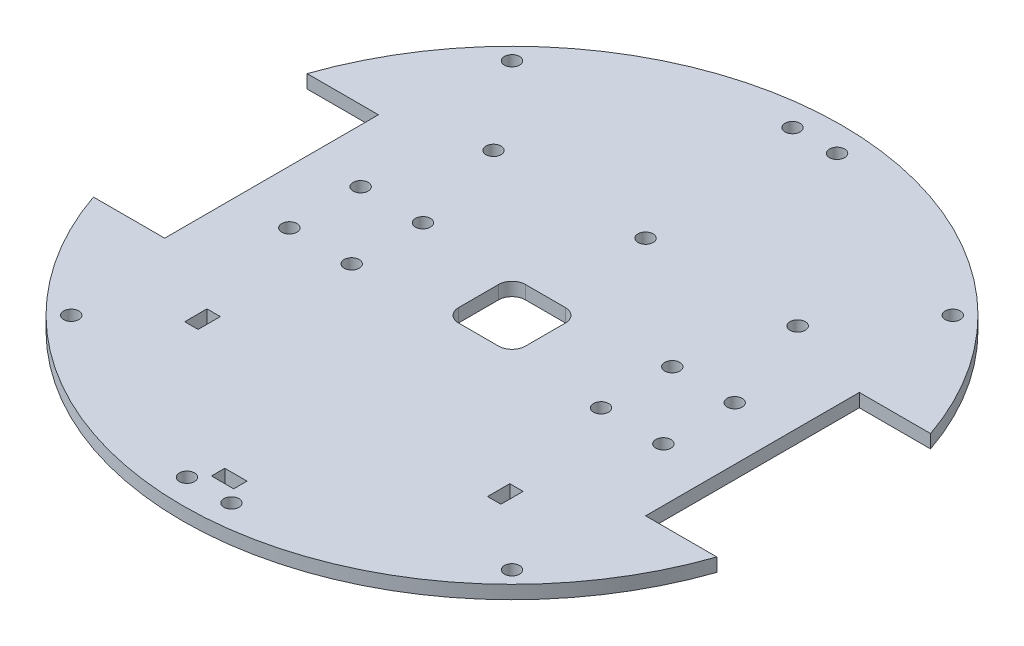
SolidWorks part; units mm, degrees
ref_plane "前视基准面" through (0, 0, 0) normal (0, 0, 1) x (1, 0, 0)
ref_plane "上视基准面" through (0, 0, 0) normal (0, 1, 0) x (1, 0, 0)
ref_plane "右视基准面" through (0, 0, 0) normal (1, 0, 0) x (0, 0, -1)
other "Configuration Table"
sketch "草图1" plane through (0, 0, 0) normal (0, 1, 0) x (1, 0, 0)
  line L0 (-74, 0) -> (74, 0) construction
  line L1 (0, 74) -> (0, -74) construction
  line L2 (35, -13) -> (35, 13) construction
  line L3 (19.5, -13) -> (50.5, -13) construction
  line L4 (19.5, -13) -> (19.5, 13) construction
  line L5 (19.5, 13) -> (50.5, 13) construction
  line L6 (50.5, -13) -> (50.5, 13) construction
  line L7 (19.5, -13) -> (50.5, 13) construction
  line L8 (19.5, 13) -> (50.5, -13) construction
  line L9 (49, 13) -> (49, -13) construction
  line L10 (70, 24) -> (54, 24)
  line L11 (54, 24) -> (54, -24)
  line L12 (54, -24) -> (70, -24)
  line L13 (-54, -24) -> (-70, -24)
  line L14 (-54, 24) -> (-54, -24)
  line L15 (-70, 24) -> (-54, 24)
  line L16 (35.5, -33) -> (32.5, -33)
  line L17 (-4.5, -7.5) -> (4.5, -7.5)
  line L18 (-7.5, -4.5) -> (-7.5, 4.5)
  line L19 (-4.5, 7.5) -> (4.5, 7.5)
  line L20 (7.5, -4.5) -> (7.5, 4.5)
  line L21 (-7.5, -7.5) -> (7.5, 7.5) construction
  line L22 (-7.5, 7.5) -> (7.5, -7.5) construction
  line L23 (-45.15, 18) -> (45.15, 18) construction
  line L24 (-45.15, 18) -> (-45.15, 55) construction
  line L25 (-45.15, 55) -> (45.15, 55) construction
  line L26 (45.15, 18) -> (45.15, 55) construction
  line L27 (-45.15, 18) -> (45.15, 55) construction
  line L28 (-45.15, 55) -> (45.15, 18) construction
  line L29 (-34, -63.5) -> (34, -63.5) construction
  line L30 (-34, -63.5) -> (-34, -7.5) construction
  line L31 (-34, -7.5) -> (34, -7.5) construction
  line L32 (34, -63.5) -> (34, -7.5) construction
  line L33 (-34, -63.5) -> (34, -7.5) construction
  line L34 (-34, -7.5) -> (34, -63.5) construction
  line L35 (-2.5, -65) -> (2.5, -65)
  line L36 (-2.5, -65) -> (-2.5, -62)
  line L37 (-2.5, -62) -> (2.5, -62)
  line L38 (2.5, -65) -> (2.5, -62)
  line L39 (-2.5, -65) -> (2.5, -62) construction
  line L40 (-2.5, -62) -> (2.5, -65) construction
  line L41 (-35.5, -38) -> (-32.5, -38)
  line L42 (-35.5, -38) -> (-35.5, -33)
  line L43 (-35.5, -33) -> (-32.5, -33)
  line L44 (-32.5, -38) -> (-32.5, -33)
  line L45 (-35.5, -38) -> (-32.5, -33) construction
  line L46 (-35.5, -33) -> (-32.5, -38) construction
  line L47 (32.5, -38) -> (32.5, -33)
  line L48 (35.5, -38) -> (32.5, -38)
  line L49 (35.5, -38) -> (35.5, -33)
  line L50 (-49.4975, -49.4975) -> (0, 0) construction
  circle A0 centre (0, 0) radius 74
  circle A1 centre (28, 8) radius 1.7
  circle A2 centre (42, 8) radius 1.7
  circle A3 centre (42, -8) radius 1.7
  circle A4 centre (28, -8) radius 1.7
  circle A5 centre (-42, -8) radius 1.7
  circle A6 centre (-28, -8) radius 1.7
  circle A7 centre (-42, 8) radius 1.7
  circle A8 centre (-28, 8) radius 1.7
  arc A9 (-4.5, 7.5) -> (-7.5, 4.5) centre (-4.5, 4.5) ccw
  arc A10 (7.5, 4.5) -> (4.5, 7.5) centre (4.5, 4.5) ccw
  arc A11 (4.5, -7.5) -> (7.5, -4.5) centre (4.5, -4.5) ccw
  arc A12 (-4.5, -7.5) -> (-7.5, -4.5) centre (-4.5, -4.5) cw
  circle A13 centre (0, 30) radius 1.7
  circle A14 centre (34.15, 30) radius 1.7
  circle A15 centre (-34.15, 30) radius 1.7
  circle A16 centre (-49.4975, -49.4975) radius 1.7
  circle A17 centre (-49.4975, 49.4975) radius 1.7
  circle A18 centre (49.4975, 49.4975) radius 1.7
  circle A19 centre (49.4975, -49.4975) radius 1.7
  circle A20 centre (5, 68) radius 1.7
  circle A21 centre (-5, 68) radius 1.7
  circle A22 centre (5, -68) radius 1.7
  circle A23 centre (-5, -68) radius 1.7
  point P3 (35, 0)
  point P6 (0, 0)
  point P10 (0, 0)
  point P20 (35, 0)
  point P59 (0, 36.5)
  point P68 (0, -35.5)
  point P75 (-34, -35.5)
  point P77 (0, -63.5)
  point P100 (0, 0)
  dimension "D1" = 148
  dimension "D4" = 8
  dimension "D13" = 15
  dimension "D15" = 3
  dimension "D16" = 3
  dimension "D17" = 3
  dimension "D18" = 3
  dimension "D22" = 12
  dimension "D26" = 5
  dimension "D28" = 4
  dimension "D29" = 5
  dimension "D2" = 26
  dimension "D3" = 31
  dimension "D5" = 7
  dimension "D8" = 1.5
  dimension "D9" = 25
  dimension "D10" = 48
  dimension "D11" = 24
  dimension "D12" = 20
  dimension "D14" = 15
  dimension "D19" = 90.3
  dimension "D20" = 37
  dimension "D21" = 5
  dimension "D23" = 11
  dimension "D24" = 68
  dimension "D25" = 56
  dimension "D27" = 3
  dimension "D30" = 6
  dimension "D6" = 2
  dimension "D7" = 2
extrude "凸台-拉伸1" add sketch "草图1" along normal blind 3 contours L10 A0 L12 L11 A7 A5 A4 A3 A2 A1 A6 A8
